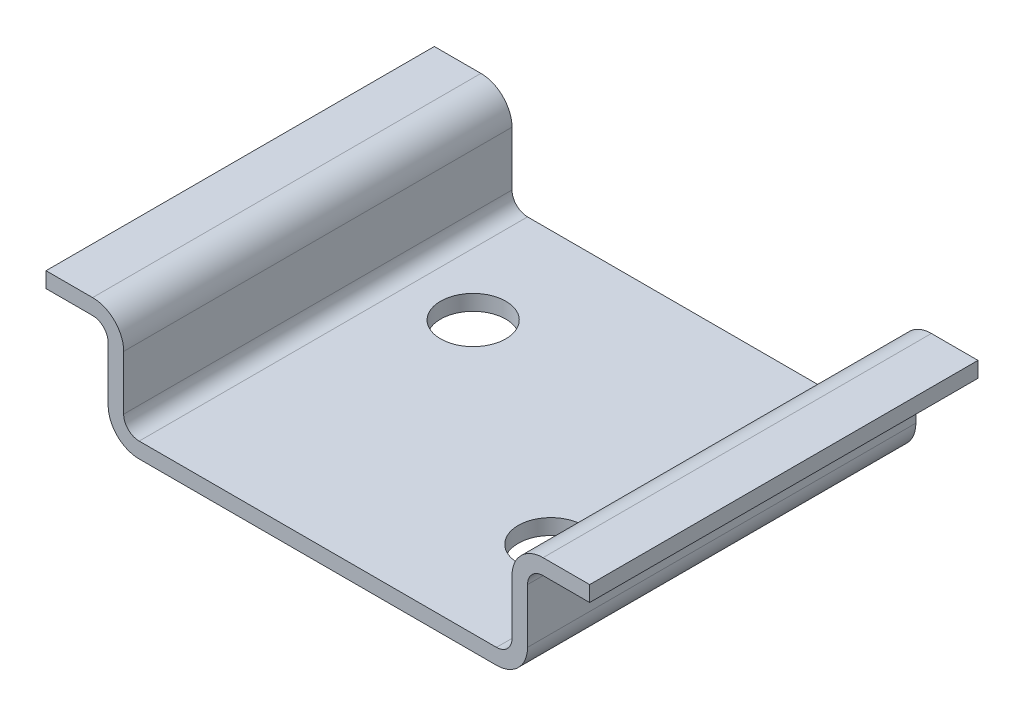
SolidWorks part; units mm, degrees
ref_plane "Спереди" through (0, 0, 0) normal (0, 0, 1) x (1, 0, 0)
ref_plane "Сверху" through (0, 0, 0) normal (0, 1, 0) x (1, 0, 0)
ref_plane "Справа" through (0, 0, 0) normal (1, 0, 0) x (0, 0, -1)
sketch "Эскиз1" plane through (0, 0, 0) normal (0, 0, 1) x (1, 0, 0)
  line L0 (0, 6.5) -> (0, -29.2061) construction
  line L1 (-17.5, 6.5) -> (-14.5, 6.5)
  line L2 (-13.5, 5.5) -> (-13.5, 2)
  line L3 (-11.5, 1) -> (11.5, 1)
  line L4 (-11.5, 0) -> (11.5, 0)
  line L5 (-12.5, 5.5) -> (-12.5, 2)
  line L6 (-17.5, 7.5) -> (-14.5, 7.5)
  line L7 (-17.5, 7.5) -> (-17.5, 6.5)
  line L8 (12.5, 5.5) -> (12.5, 2)
  line L9 (13.5, 5.5) -> (13.5, 2)
  line L10 (17.5, 6.5) -> (14.5, 6.5)
  line L11 (17.5, 7.5) -> (17.5, 6.5)
  line L12 (17.5, 7.5) -> (14.5, 7.5)
  arc A0 (-14.5, 6.5) -> (-13.5, 5.5) centre (-14.5, 5.5) cw
  arc A1 (13.5, 2) -> (11.5, 0) centre (11.5, 2) cw
  arc A2 (-14.5, 7.5) -> (-12.5, 5.5) centre (-14.5, 5.5) cw
  arc A3 (-13.5, 2) -> (-11.5, 0) centre (-11.5, 2) ccw
  arc A4 (14.5, 7.5) -> (12.5, 5.5) centre (14.5, 5.5) ccw
  arc A5 (14.5, 6.5) -> (13.5, 5.5) centre (14.5, 5.5) ccw
  arc A6 (-11.5, 1) -> (-12.5, 2) centre (-11.5, 2) cw
  arc A7 (12.5, 2) -> (11.5, 1) centre (11.5, 2) cw
  point P9 (-13.5, 6.5)
  point P11 (13.5, 0)
  point P12 (-13.5, 0)
  point P18 (0, 0)
  point P19 (0, 1)
  point P34 (-13.5, 0)
  dimension "D1" = 13.5
  dimension "D2" = 6.5
  dimension "D3" = 17.5
  dimension "D5" = 1
extrude "Вытянуть1" add sketch "Эскиз1" along normal blind 90
sketch "Эскиз3" plane through (0, 0, 90) normal (0, 0, 1) x (1, 0, 0)
  line L12 (-17.5, 7.5) -> (-17.5, 6.5)
  line L13 (-17.5, 6.5) -> (-14.5, 6.5)
  line L14 (-13.5, 5.5) -> (-13.5, 2)
  line L15 (-11.5, 0) -> (11.5, 0)
  line L16 (13.5, 2) -> (13.5, 5.5)
  line L17 (14.5, 6.5) -> (17.5, 6.5)
  line L18 (17.5, 6.5) -> (17.5, 7.5)
  line L19 (17.5, 7.5) -> (14.5, 7.5)
  line L20 (12.5, 5.5) -> (12.5, 2)
  line L21 (11.5, 1) -> (-11.5, 1)
  line L22 (-12.5, 2) -> (-12.5, 5.5)
  line L23 (-14.5, 7.5) -> (-17.5, 7.5)
  line L24 (-17.5, 7.5) -> (-17.5, 6.5)
  line L25 (-17.5, 6.5) -> (-14.5, 6.5)
  line L26 (-13.5, 5.5) -> (-13.5, 2)
  line L27 (-11.5, 0) -> (11.5, 0)
  line L28 (13.5, 2) -> (13.5, 5.5)
  line L29 (14.5, 6.5) -> (17.5, 6.5)
  line L30 (17.5, 6.5) -> (17.5, 7.5)
  line L31 (17.5, 7.5) -> (14.5, 7.5)
  line L32 (12.5, 5.5) -> (12.5, 2)
  line L33 (11.5, 1) -> (-11.5, 1)
  line L34 (-12.5, 2) -> (-12.5, 5.5)
  line L35 (-14.5, 7.5) -> (-17.5, 7.5)
  arc A8 (-13.5, 5.5) -> (-14.5, 6.5) centre (-14.5, 5.5) ccw
  arc A9 (-13.5, 2) -> (-11.5, 0) centre (-11.5, 2) ccw
  arc A10 (11.5, 0) -> (13.5, 2) centre (11.5, 2) ccw
  arc A11 (14.5, 6.5) -> (13.5, 5.5) centre (14.5, 5.5) ccw
  arc A12 (14.5, 7.5) -> (12.5, 5.5) centre (14.5, 5.5) ccw
  arc A13 (11.5, 1) -> (12.5, 2) centre (11.5, 2) ccw
  arc A14 (-12.5, 2) -> (-11.5, 1) centre (-11.5, 2) ccw
  arc A15 (-12.5, 5.5) -> (-14.5, 7.5) centre (-14.5, 5.5) ccw
  arc A16 (-13.5, 5.5) -> (-14.5, 6.5) centre (-14.5, 5.5) ccw
  arc A17 (-13.5, 2) -> (-11.5, 0) centre (-11.5, 2) ccw
  arc A18 (11.5, 0) -> (13.5, 2) centre (11.5, 2) ccw
  arc A19 (14.5, 6.5) -> (13.5, 5.5) centre (14.5, 5.5) ccw
  arc A20 (14.5, 7.5) -> (12.5, 5.5) centre (14.5, 5.5) ccw
  arc A21 (11.5, 1) -> (12.5, 2) centre (11.5, 2) ccw
  arc A22 (-12.5, 2) -> (-11.5, 1) centre (-11.5, 2) ccw
  arc A23 (-12.5, 5.5) -> (-14.5, 7.5) centre (-14.5, 5.5) ccw
  dimension "D1" = 0
extrude "Вырез-Вытянуть2" cut sketch "Эскиз3" against normal blind 65
sketch "Эскиз4" plane through (0, 1, 0) normal (0, 1, 0) x (-1, 0, 0)
  line L0 (0, -2.8424) -> (0, 26.6761) construction
  line L1 (-11.5, 0) -> (11.5, 0) construction
  circle A0 centre (7.5, 7.5) radius 2.1
  circle A1 centre (-7.5, 17.5) radius 2.1
  dimension "D1" = 15
  dimension "D2" = 10
  dimension "D3" = 7.5
  dimension "D4" = 7.5
  dimension "D5" = 4.2
extrude "Вырез-Вытянуть3" cut sketch "Эскиз4" against normal blind 10
